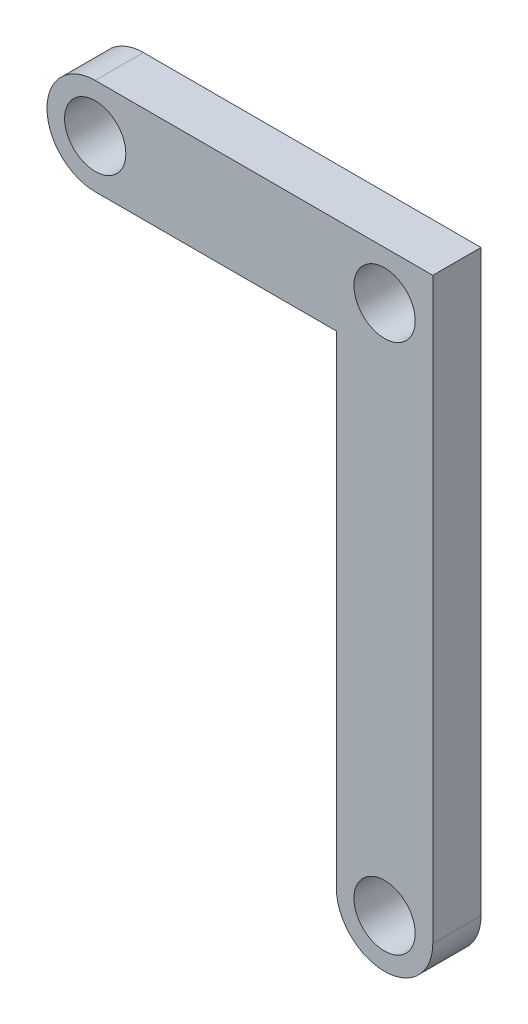
SolidWorks part; units mm, degrees
ref_plane "Alzado" through (0, 0, 0) normal (0, 0, 1) x (1, 0, 0)
ref_plane "Planta" through (0, 0, 0) normal (0, 1, 0) x (1, 0, 0)
ref_plane "Vista lateral" through (0, 0, 0) normal (1, 0, 0) x (0, 0, -1)
sketch "Croquis1" plane through (0, 0, 0) normal (0, 0, 1) x (1, 0, 0)
  line L0 (0, 0) -> (0, -50)
  line L1 (0, 0) -> (-25, 0)
  line L2 (10, 10) -> (10, -50)
  line L3 (10, 10) -> (-25, 10)
  arc A0 (0, -50) -> (10, -50) centre (5, -50) ccw
  arc A1 (-25, 0) -> (-25, 10) centre (-25, 5) cw
  circle A2 centre (5, -50) radius 3.175
  circle A3 centre (5, 5) radius 3.175
  circle A4 centre (-25, 5) radius 3.175
  point P15 (0, 0)
  point P16 (0, 0)
  dimension "D4" = 6.35
  dimension "D2" = 60
  dimension "D3" = 35
  dimension "D1" = 10
extrude "Saliente-Extruir1" add sketch "Croquis1" along normal mid plane 5
